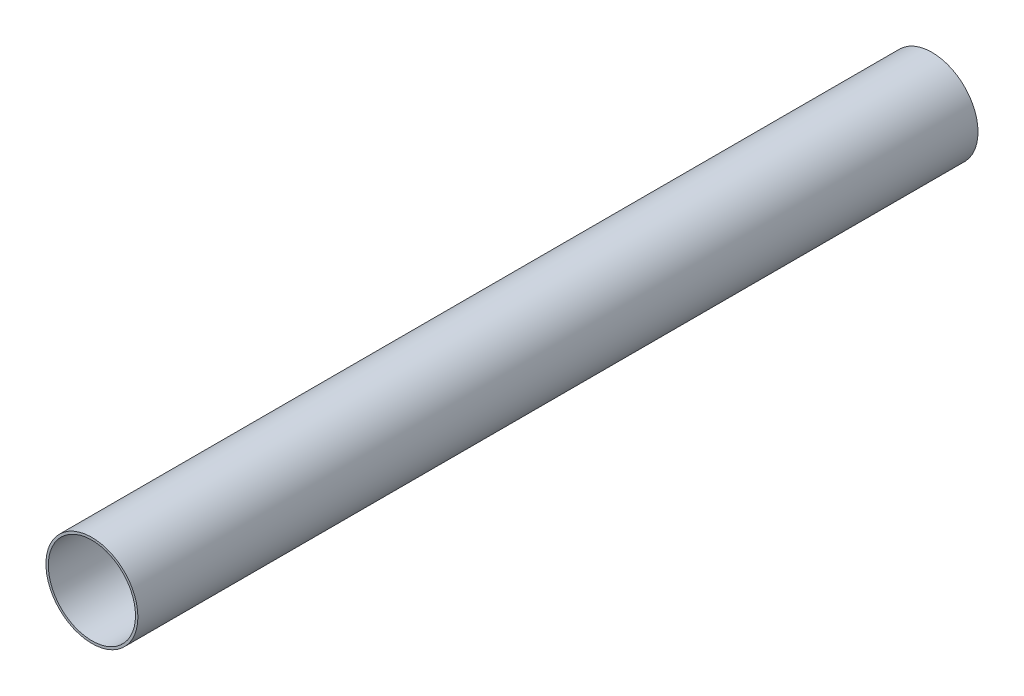
SolidWorks part; units mm, degrees
material "Corrugated Paper"
ref_plane "Front Plane" through (0, 0, 0) normal (0, 0, 1) x (1, 0, 0)
ref_plane "Top Plane" through (0, 0, 0) normal (0, 1, 0) x (1, 0, 0)
ref_plane "Right Plane" through (0, 0, 0) normal (1, 0, 0) x (0, 0, -1)
sketch "Sketch1" plane through (0, 0, 0) normal (0, 0, 1) x (1, 0, 0)
  circle A0 centre (0, 0) radius 14.5
  circle A1 centre (0, 0) radius 15.2937
  dimension "D1" = 0.7937
  dimension "D2" = 29
extrude "Boss-Extrude1" add sketch "Sketch1" along normal blind 279.4
